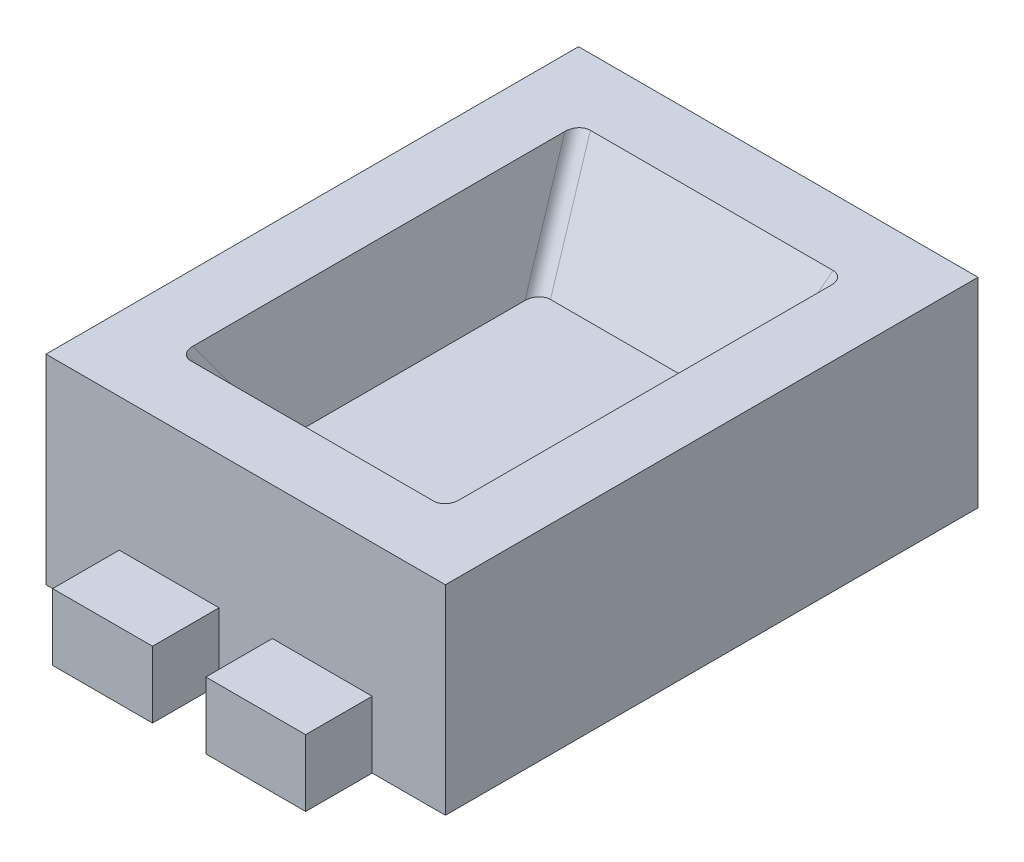
SolidWorks part; units mm, degrees
ref_plane "Alzado" through (0, 0, 0) normal (0, 0, 1) x (1, 0, 0)
ref_plane "Planta" through (0, 0, 0) normal (0, 1, 0) x (1, 0, 0)
ref_plane "Vista lateral" through (0, 0, 0) normal (1, 0, 0) x (0, 0, -1)
sketch "Croquis1" plane through (0, 0, 0) normal (0, 0, 1) x (1, 0, 0)
  line L0 (0, 1.2975) -> (0, -1.4114) construction
  line L5 (-1.5, 0) -> (1.5, 0)
  line L6 (1.5, 0) -> (1.5, 1.5)
  line L7 (1.5, 1.5) -> (1, 1.5)
  line L8 (1, 1.5) -> (0.8, 0.75)
  line L9 (0.8, 0.75) -> (-0.8, 0.75)
  line L10 (-1, 1.5) -> (-0.8, 0.75)
  line L11 (-1.5, 1.5) -> (-1, 1.5)
  line L12 (-1.5, 0) -> (-1.5, 1.5)
  point P10 (0, 0)
  point P13 (0, 0.75)
  dimension "D1" = 1.5
  dimension "D2" = 0.5
  dimension "D3" = 1.5
  dimension "D4" = 0.2
  dimension "D5" = 0.75
extrude "Saliente-Extruir1" add sketch "Croquis1" along normal mid plane 3
sketch "Croquis2" plane through (0, 0, 0) normal (1, 0, 0) x (0, 0, -1)
  line L4 (0, 2.1055) -> (0, -0.6101) construction
  line L6 (1, 0) -> (2, 0)
  line L7 (2, 0) -> (2, 1.5)
  line L8 (2, 1.5) -> (1.5, 1.5)
  line L9 (1.5, 0) -> (1.5, 1.5) construction
  line L10 (1.5, 1.5) -> (1, 0.75)
  line L11 (1, 0.75) -> (1, 0)
  line L12 (-1.5, 0) -> (1.5, 0) construction
  line L13 (-1, 0.75) -> (-1, 0)
  line L14 (-1.5, 1.5) -> (-1, 0.75)
  line L15 (-2, 1.5) -> (-1.5, 1.5)
  line L16 (-2, 0) -> (-2, 1.5)
  line L17 (-1, 0) -> (-2, 0)
  dimension "D1" = 1.5
  dimension "D2" = 0.5
  dimension "D3" = 1
  dimension "D4" = 0.75
extrude "Saliente-Extruir2" add sketch "Croquis2" along normal mid plane 3
fillet "Redondeo2" radius 0.1 4 edges at (0.9, 1.125, 1.25) (0.9, 1.125, -1.25) (-0.9, 1.125, -1.25) (-0.9, 1.125, 1.25)
sketch "Croquis3" plane through (0, 0, 2) normal (0, 0, 1) x (1, 0, 0)
  line L0 (1.5, 0) -> (-1.5, 0) construction
  line L1 (-0.95, 0) -> (-0.2, 0)
  line L2 (-0.95, 0) -> (-0.95, 0.5)
  line L3 (-0.95, 0.5) -> (-0.2, 0.5)
  line L4 (-0.2, 0) -> (-0.2, 0.5)
  line L6 (0.2, 0) -> (0.95, 0)
  line L7 (0.2, 0) -> (0.2, 0.5)
  line L8 (0.2, 0.5) -> (0.95, 0.5)
  line L9 (0.95, 0) -> (0.95, 0.5)
  dimension "D1" = 0.5
  dimension "D2" = 0.75
  dimension "D3" = 0.2
  dimension "D4" = 0.2
extrude "Saliente-Extruir3" add sketch "Croquis3" along normal blind 0.5
mirror "Simetría1" about plane through (0, 0, 0) normal (0, 0, 1) of "Saliente-Extruir3"
equation "\"D4@Croquis3\"=\"D3@Croquis3\""
